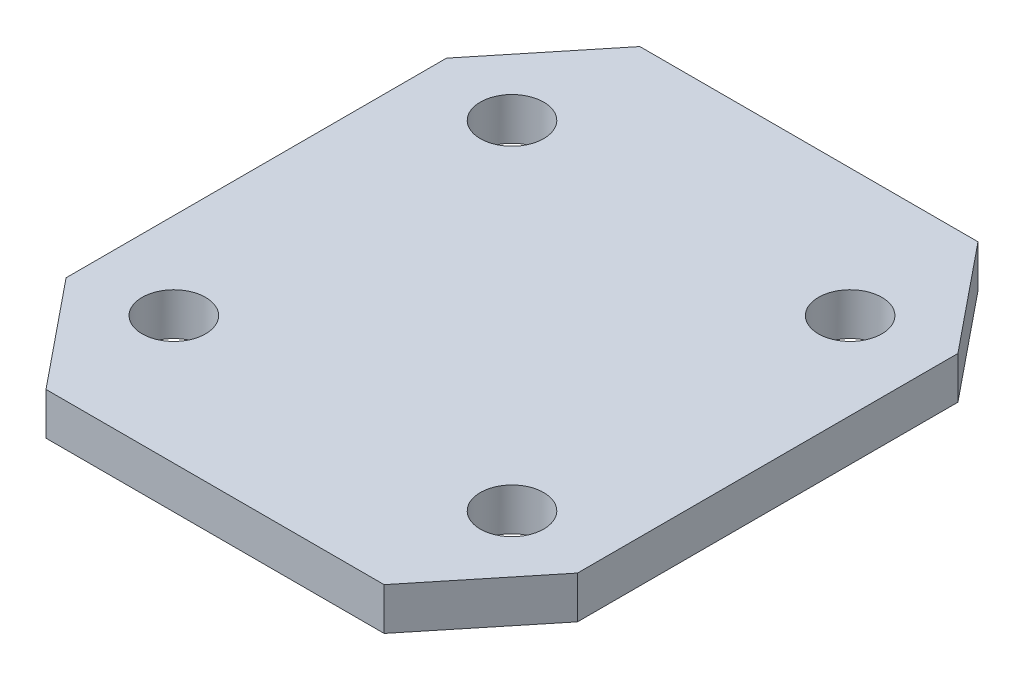
SolidWorks part; units mm, degrees
ref_plane "Front" through (0, 0, 0) normal (0, 0, 1) x (1, 0, 0)
ref_plane "Top" through (0, 0, 0) normal (0, 1, 0) x (1, 0, 0)
ref_plane "Right" through (0, 0, 0) normal (1, 0, 0) x (0, 0, -1)
sketch "Sketch1" plane through (0, 0, 0) normal (0, 1, 0) x (1, 0, 0)
  line L0 (-12.1, 9) -> (-8, 14.05)
  line L1 (-8, -14.05) -> (8, -14.05)
  line L2 (-12.1, -9) -> (-12.1, 9)
  line L3 (-8, 14.05) -> (8, 14.05)
  line L4 (12.1, -9) -> (12.1, 9)
  line L5 (-8, -14.05) -> (8, 14.05) construction
  line L6 (-8, 14.05) -> (8, -14.05) construction
  line L7 (8, 14.05) -> (12.1, 9)
  line L8 (-12.1, -9) -> (-8, -14.05)
  line L9 (8, -14.05) -> (12.1, -9)
  line L14 (-12.1, 0) -> (12.1, 0) construction
  line L15 (0, 14.05) -> (0, -14.05) construction
  point P0 (0, 0)
  point P3 (-12.1, 6.6946)
  point P4 (12.1, 9.9642)
  dimension "D1" = 28.1
  dimension "D2" = 24.2
  dimension "D3" = 16
  dimension "D4" = 18
extrude "Boss-Extrude1" add sketch "Sketch1" along normal blind 2
sketch "Sketch2" plane through (0, 2, 0) normal (0, 1, 0) x (1, 0, 0)
  line L0 (-8, -8) -> (8, 8) construction
  line L1 (-8, 8) -> (8, -8) construction
  line L2 (-8, -8) -> (8, -8) construction
  line L3 (8, 8) -> (8, -8) construction
  line L4 (-8, -8) -> (-8, 8) construction
  line L5 (-8, 8) -> (8, 8) construction
  circle A0 centre (-8, 8) radius 1.5
  circle A1 centre (8, 8) radius 1.5
  circle A2 centre (-8, -8) radius 1.5
  circle A3 centre (8, -8) radius 1.5
  point P8 (-6.4589, 5.107)
  point P9 (-7.8858, 8.4116)
  dimension "D3" = 3
  dimension "D1" = 16
  dimension "D2" = 16
extrude "Cut-Extrude1" cut sketch "Sketch2" against normal blind 10
